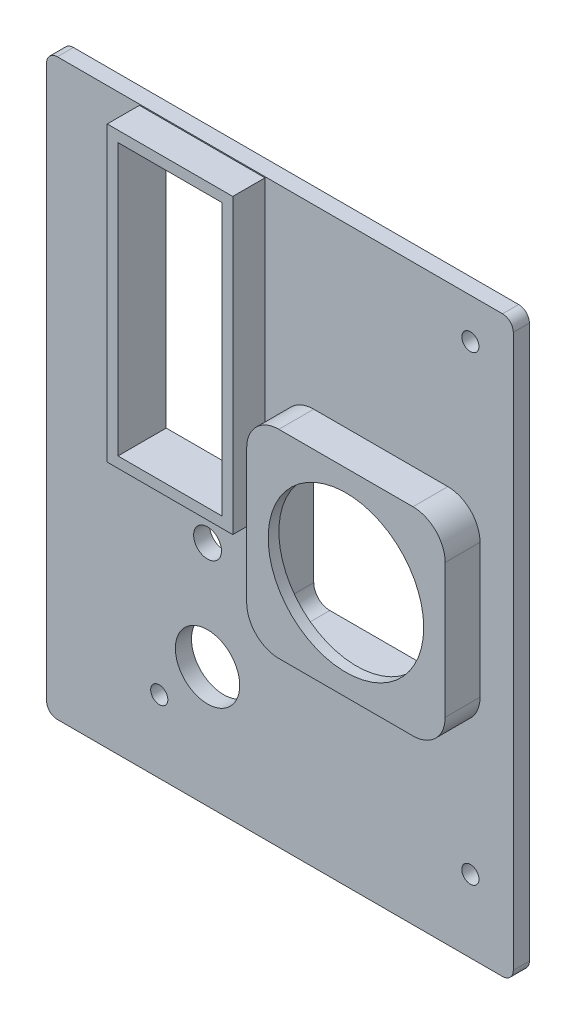
SolidWorks part; units mm, degrees
ref_plane "Ön Düzlem" through (0, 0, 0) normal (0, 0, 1) x (1, 0, 0)
ref_plane "Üst Düzlem" through (0, 0, 0) normal (0, 1, 0) x (1, 0, 0)
ref_plane "Sağ Düzlem" through (0, 0, 0) normal (1, 0, 0) x (0, 0, -1)
sketch "Çizim1" plane through (0, 0, 0) normal (0, 0, 1) x (1, 0, 0)
  line L1 (-40.5, 50.5) -> (40.5, 50.5) construction
  line L2 (-40.5, 50.5) -> (-40.5, -50.5) construction
  line L3 (-40.5, -50.5) -> (40.5, -50.5) construction
  line L4 (40.5, 50.5) -> (40.5, -50.5) construction
  line L5 (-40.5, 50.5) -> (40.5, -50.5) construction
  line L6 (-40.5, -50.5) -> (40.5, 50.5) construction
  line L7 (-43.5, 53.5) -> (43.5, 53.5)
  line L8 (-43.5, 53.5) -> (-43.5, -53.5)
  line L9 (-43.5, -53.5) -> (43.5, -53.5)
  line L10 (43.5, 53.5) -> (43.5, -53.5)
  line L11 (-43.5, 53.5) -> (43.5, -53.5) construction
  line L12 (-43.5, -53.5) -> (43.5, 53.5) construction
  point P0 (0, 0)
  point P6 (0, 0)
  dimension "D1" = 81
  dimension "D2" = 101
  dimension "D3" = 3
  dimension "D4" = 3
extrude "Tapa" add sketch "Çizim1" along normal blind 3
fillet "Redondeo1" radius 2 4 edges at (-43.5, -53.5, 1.5) (43.5, -53.5, 1.5) (43.5, 53.5, 1.5) (-43.5, 53.5, 1.5)
sketch "Çizim3" plane through (0, 0, 3) normal (0, 0, 1) x (1, 0, 0)
  line L0 (35.5, 46) -> (35.5, -40) construction
  line L1 (39.5, 50) -> (-39.5, 50) construction
  line L2 (39.5, 50) -> (39.5, -50) construction
  line L3 (39.5, -50) -> (-39.5, -50) construction
  line L4 (-39.5, 50) -> (-39.5, -50) construction
  line L5 (39.5, 50) -> (-39.5, -50) construction
  line L6 (39.5, -50) -> (-39.5, 50) construction
  line L7 (35.5, 3) -> (6.5, 3) construction
  line L8 (6.5, 3) -> (6.5, -7.9948) construction
  circle A0 centre (35.5, 46) radius 1.6
  circle A1 centre (35.5, -40) radius 1.6
  circle A2 centre (-22.5, 46) radius 1.6
  circle A3 centre (-22.5, -40) radius 1.6
  point P0 (0, 0)
  dimension "D3" = 4
  dimension "D4" = 4
  dimension "D6" = 3.2
  dimension "D7" = 3.2
  dimension "D1" = 100
  dimension "D2" = 79
  dimension "D5" = 86
  dimension "D8" = 29
extrude "HuecosPlaca" cut sketch "Çizim3" against normal blind 3
sketch "Çizim2" plane through (0, 0, 3) normal (0, 0, 1) x (1, 0, 0)
  line L0 (43.5, -51.5) -> (43.5, 51.5) construction
  line L1 (41.5, 53.5) -> (-41.5, 53.5) construction
  line L2 (34.8, 18) -> (34.8, -14) construction
  line L3 (34.8, 2) -> (18.8, 2) construction
  line L4 (18.8, 2) -> (18.8, -7.7341) construction
  circle A0 centre (34.8, 18) radius 1.6
  circle A1 centre (34.8, -14) radius 1.6
  circle A2 centre (2.8, -14) radius 1.6
  circle A3 centre (2.8, 18) radius 1.6
  dimension "D2" = 35.5
  dimension "D3" = 3.2
  dimension "D5" = 3.2
  dimension "D1" = 8.7
  dimension "D4" = 32
  dimension "D6" = 16
  dimension "D7" = 9.7341
extrude "HuecoDisipador" cut sketch "Çizim2" against normal blind 3
sketch "Croquis1" plane through (0, 0, 3) normal (0, 0, 1) x (1, 0, 0)
  line L0 (2.8, 18) -> (34.8, -14) construction
  line L7 (6.3, -13.5) -> (31.3, -13.5)
  line L8 (3.3, -10.5) -> (3.3, 14.5)
  line L9 (6.3, 17.5) -> (31.3, 17.5)
  line L10 (34.3, -10.5) -> (34.3, 14.5)
  line L11 (3.3, -13.5) -> (34.3, 17.5) construction
  line L12 (3.3, 17.5) -> (34.3, -13.5) construction
  arc A0 (6.3, -13.5) -> (3.3, -10.5) centre (6.3, -10.5) cw
  arc A1 (31.3, -13.5) -> (34.3, -10.5) centre (31.3, -10.5) ccw
  arc A2 (3.3, 14.5) -> (6.3, 17.5) centre (6.3, 14.5) cw
  arc A3 (31.3, 17.5) -> (34.3, 14.5) centre (31.3, 14.5) cw
  point P4 (18.8, 2)
  dimension "D3" = 3
  dimension "D1" = 31
  dimension "D2" = 31
extrude "HuecoFan" cut sketch "Croquis1" against normal blind 10
sketch "Croquis7" plane through (0, 0, 3) normal (0, 0, 1) x (1, 0, 0)
  line L20 (6.3, -16.5) -> (31.3, -16.5)
  line L21 (37.3, -10.5) -> (37.3, 14.5)
  line L22 (31.3, 20.5) -> (6.3, 20.5)
  line L23 (0.3, 14.5) -> (0.3, -10.5)
  line L24 (6.3, -13.5) -> (31.3, -13.5)
  line L25 (34.3, -10.5) -> (34.3, 14.5)
  line L26 (31.3, 17.5) -> (6.3, 17.5)
  line L27 (3.3, 14.5) -> (3.3, -10.5)
  line L28 (6.3, -13.5) -> (31.3, -13.5)
  line L29 (34.3, -10.5) -> (34.3, 14.5)
  line L30 (31.3, 17.5) -> (6.3, 17.5)
  line L31 (3.3, 14.5) -> (3.3, -10.5)
  arc A16 (31.3, -16.5) -> (37.3, -10.5) centre (31.3, -10.5) ccw
  arc A17 (37.3, 14.5) -> (31.3, 20.5) centre (31.3, 14.5) ccw
  arc A18 (6.3, 20.5) -> (0.3, 14.5) centre (6.3, 14.5) ccw
  arc A19 (0.3, -10.5) -> (6.3, -16.5) centre (6.3, -10.5) ccw
  arc A20 (3.3, -10.5) -> (6.3, -13.5) centre (6.3, -10.5) ccw
  arc A21 (31.3, -13.5) -> (34.3, -10.5) centre (31.3, -10.5) ccw
  arc A22 (34.3, 14.5) -> (31.3, 17.5) centre (31.3, 14.5) ccw
  arc A23 (6.3, 17.5) -> (3.3, 14.5) centre (6.3, 14.5) ccw
  arc A24 (3.3, -10.5) -> (6.3, -13.5) centre (6.3, -10.5) ccw
  arc A25 (31.3, -13.5) -> (34.3, -10.5) centre (31.3, -10.5) ccw
  arc A26 (34.3, 14.5) -> (31.3, 17.5) centre (31.3, 14.5) ccw
  arc A27 (6.3, 17.5) -> (3.3, 14.5) centre (6.3, 14.5) ccw
  dimension "D1" = 0
  dimension "D2" = 3
extrude "Saliente-Extruir4" add sketch "Croquis7" along normal blind 4.5
sketch "Croquis8" plane through (0, 0, 0) normal (0, 0, -1) x (-1, 0, 0)
  line L1 (-37.307, -16.846) -> (0, -16.846)
  line L2 (-37.307, -16.846) -> (-37.307, 21.907)
  line L3 (-37.307, 21.907) -> (0, 21.907)
  line L4 (0, -16.846) -> (0, 21.907)
  line L6 (-34.3, -10.5) -> (-34.3, 14.5) construction
  line L31 (-3.3, -10.5) -> (-3.3, 14.5)
  line L32 (-34.3, 14.5) -> (-34.3, -10.5)
  line L33 (-31.3, -13.5) -> (-6.3, -13.5)
  line L34 (-6.3, 17.5) -> (-31.3, 17.5)
  line L35 (-3.3, -10.5) -> (-3.3, 14.5)
  line L36 (-34.3, 14.5) -> (-34.3, -10.5)
  line L37 (-31.3, -13.5) -> (-6.3, -13.5)
  line L38 (-6.3, 17.5) -> (-31.3, 17.5)
  arc A24 (-6.3, -13.5) -> (-3.3, -10.5) centre (-6.3, -10.5) ccw
  arc A25 (-3.3, 14.5) -> (-6.3, 17.5) centre (-6.3, 14.5) ccw
  arc A26 (-34.3, -10.5) -> (-31.3, -13.5) centre (-31.3, -10.5) ccw
  arc A27 (-31.3, 17.5) -> (-34.3, 14.5) centre (-31.3, 14.5) ccw
  arc A28 (-6.3, -13.5) -> (-3.3, -10.5) centre (-6.3, -10.5) ccw
  arc A29 (-3.3, 14.5) -> (-6.3, 17.5) centre (-6.3, 14.5) ccw
  arc A30 (-34.3, -10.5) -> (-31.3, -13.5) centre (-31.3, -10.5) ccw
  arc A31 (-31.3, 17.5) -> (-34.3, 14.5) centre (-31.3, 14.5) ccw
  dimension "D1" = 0
extrude "Saliente-Extruir5" add sketch "Croquis8" against normal up to surface (3 mm away) up to face at (18.8, 2, 3)
sketch "Croquis9" plane through (0, 0, 7.5) normal (0, 0, 1) x (1, 0, 0)
  line L4 (18.8, 17.5) -> (18.8, -13.5) construction
  line L5 (31.3, 17.5) -> (6.3, 17.5) construction
  line L6 (6.3, -13.5) -> (31.3, -13.5) construction
  line L8 (6.3, -16.5) -> (31.3, -16.5)
  line L9 (37.3, -10.5) -> (37.3, 14.5)
  line L10 (31.3, 20.5) -> (6.3, 20.5)
  line L11 (0.3, 14.5) -> (0.3, -10.5)
  line L12 (6.3, -16.5) -> (31.3, -16.5)
  line L13 (37.3, -10.5) -> (37.3, 14.5)
  line L14 (31.3, 20.5) -> (6.3, 20.5)
  line L15 (0.3, 14.5) -> (0.3, -10.5)
  circle A4 centre (18.8, 2) radius 14.5
  arc A8 (0.3, -10.5) -> (6.3, -16.5) centre (6.3, -10.5) ccw
  arc A9 (31.3, -16.5) -> (37.3, -10.5) centre (31.3, -10.5) ccw
  arc A10 (37.3, 14.5) -> (31.3, 20.5) centre (31.3, 14.5) ccw
  arc A11 (6.3, 20.5) -> (0.3, 14.5) centre (6.3, 14.5) ccw
  arc A12 (0.3, -10.5) -> (6.3, -16.5) centre (6.3, -10.5) ccw
  arc A13 (31.3, -16.5) -> (37.3, -10.5) centre (31.3, -10.5) ccw
  arc A14 (37.3, 14.5) -> (31.3, 20.5) centre (31.3, 14.5) ccw
  arc A15 (6.3, 20.5) -> (0.3, 14.5) centre (6.3, 14.5) ccw
  dimension "D2" = 29
  dimension "D1" = 0
extrude "Saliente-Extruir6" add sketch "Croquis9" along normal blind 2
sketch "Croquis10" plane through (0, 0, 3) normal (0, 0, 1) x (1, 0, 0)
  line L0 (-43.5, 51.5) -> (-43.5, -51.5) construction
  line L1 (-41.5, -53.5) -> (41.5, -53.5) construction
  line L2 (-13.5, -31) -> (-13.5, -11) construction
  circle A0 centre (-13.5, -11) radius 2.6
  circle A1 centre (-13.5, -31) radius 6
  dimension "D2" = 5.2
  dimension "D3" = 12
  dimension "D5" = 22.5
  dimension "D1" = 20
  dimension "D4" = 30
extrude "LEDandBUZZER" cut sketch "Croquis10" against normal blind 10
sketch "Croquis11" plane through (0, 0, 3) normal (0, 0, 1) x (1, 0, 0)
  line L0 (-43.5, 51.5) -> (-43.5, -51.5) construction
  line L1 (41.5, 53.5) -> (-41.5, 53.5) construction
  line L3 (-4.8, 51.3) -> (-24.2, 51.3)
  line L4 (-4.8, 51.3) -> (-4.8, 0.7)
  line L5 (-4.8, 0.7) -> (-24.2, 0.7)
  line L6 (-24.2, 51.3) -> (-24.2, 0.7)
  line L7 (-4.8, 51.3) -> (-24.2, 0.7) construction
  line L8 (-4.8, 0.7) -> (-24.2, 51.3) construction
  point P0 (-14.5, 26)
  dimension "D1" = 29
  dimension "D2" = 19.4
  dimension "D3" = 50.6
  dimension "D4" = 27.5
extrude "DISPLAY" cut sketch "Croquis11" against normal blind 10
sketch "Croquis12" plane through (0, 0, 3) normal (0, 0, 1) x (1, 0, 0)
  line L0 (-26.2, 53.3) -> (-2.8, 53.3)
  line L1 (-24.2, 51.3) -> (-4.8, 51.3)
  line L2 (-24.2, 51.3) -> (-24.2, 0.7)
  line L3 (-24.2, 0.7) -> (-4.8, 0.7)
  line L4 (-4.8, 51.3) -> (-4.8, 0.7)
  line L5 (-2.8, 53.3) -> (-2.8, -1.3)
  line L6 (-26.2, -1.3) -> (-2.8, -1.3)
  line L7 (-26.2, 53.3) -> (-26.2, -1.3)
  dimension "D1" = 2
extrude "Saliente-Extruir7" add sketch "Croquis12" along normal blind 6
